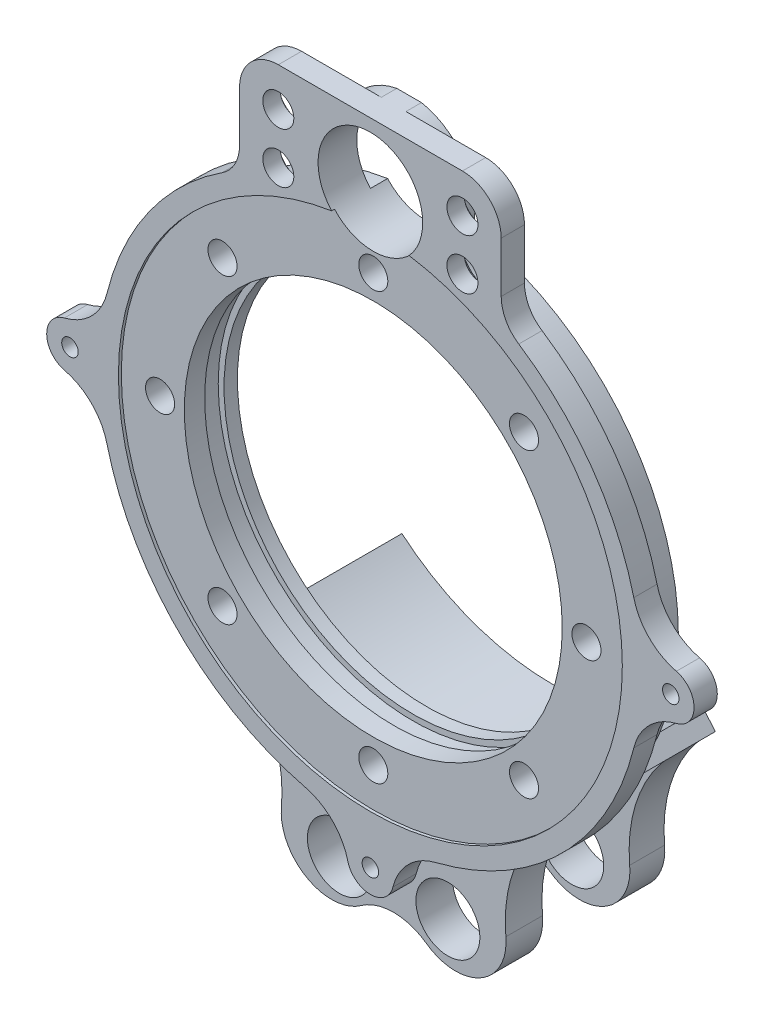
SolidWorks part; units mm, degrees
ref_plane "Front Plane" through (0, 0, 0) normal (0, 0, 1) x (1, 0, 0)
ref_plane "Top Plane" through (0, 0, 0) normal (0, 1, 0) x (1, 0, 0)
ref_plane "Right Plane" through (0, 0, 0) normal (1, 0, 0) x (0, 0, -1)
sketch "Sketch2" plane through (0, 0, 0) normal (0, 0, 1) x (1, 0, 0)
  circle A0 centre (0, 0) radius 140
  circle A1 centre (0, 0) radius 130
  dimension "D1" = 280
  dimension "D2" = 260
extrude "ВнешняяОкружность" add sketch "Sketch2" against normal blind 12
sketch "Sketch3" plane through (0, 0, 0) normal (0, 0, 1) x (1, 0, 0)
  circle A0 centre (0, 0) radius 130
  circle A1 centre (0, 0) radius 97.5
  circle A2 centre (0, 0) radius 130 construction
  dimension "D1" = 195
extrude "ВнутренняяОкружность" add sketch "Sketch3" against normal blind 27.4 from offset 1.5 offset against normal yes
sketch "Sketch4" plane through (0, 0, 0) normal (0, 0, 1) x (1, 0, 0)
  line L0 (0, 422.0044) -> (0, -162.0044) construction
  line L1 (-172.5138, 0) -> (190.2581, 0) construction
  line L2 (-67.5, 111.1024) -> (-67.5, 180)
  line L3 (67.5, 111.1024) -> (67.5, 180)
  line L4 (-67.5, 180) -> (67.5, 180)
  circle A0 centre (0, 0) radius 140 construction
  arc A4 (-67.5, 111.1024) -> (67.5, 111.1024) centre (0, 0) cw
  circle A5 centre (0, 0) radius 130 construction
  spline S0 degree 1 poles (-67.5, 180) (-67.5, 122.653) knots 0 0 1 1
  spline S1 degree 1 poles (67.5, 180) (67.5, 122.653) knots 0 0 1 1
  point P10 (0, 130)
  point P13 (0, 180)
  dimension "D1" = 40
  dimension "D2" = 135
extrude "ВерхнееПриспособление" add sketch "Sketch4" against normal up to surface (12 mm away) contours L4 L3 A4 L2 up to face at (130, 0, -12)
fillet "ВерхПриспосОкругл1" radius 20 2 edges at (-67.5, 180, -6) (67.5, 180, -6)
fillet "ВерхПриспосОкругл2" radius 20 2 edges at (67.5, 122.653, -6) (-67.5, 122.653, -6)
sketch "Sketch5" plane through (0, 0, 0) normal (0, 0, 1) x (1, 0, 0)
  line L0 (0, 277.4091) -> (0, -201.1036) construction
  line L1 (47.5, 206.683) -> (47.5, 65.5198) construction
  line L2 (-92.0038, 133.9543) -> (83.972, 133.9543) construction
  line L4 (-47.5, 180) -> (47.5, 180) construction
  line L5 (-92.0038, 160) -> (83.972, 160) construction
  line L6 (-47.5, 206.683) -> (-47.5, 65.5198) construction
  circle A0 centre (0, 146.6) radius 27
  circle A1 centre (-47.5, 160) radius 8
  circle A2 centre (47.5, 160) radius 8
  circle A3 centre (-47.5, 133.9543) radius 8
  circle A4 centre (47.5, 133.9543) radius 8
  dimension "D1" = 54
  dimension "D3" = 16
  dimension "D4" = 16
  dimension "D5" = 16
  dimension "D6" = 16
  dimension "D2" = 6.4
extrude "ВерхПриспосОтверстия" cut sketch "Sketch5" against normal through all both and the other way through all
sketch "Sketch7" plane through (0, 0, 0) normal (0, 0, 1) x (1, 0, 0)
  line L0 (-47.5, 180) -> (47.5, 180) construction
  line L1 (-6.3592, 180) -> (6.3592, 180)
  arc A0 (-6.3592, 180) -> (6.3592, 180) centre (0, 146.6) ccw
  circle A1 centre (0, 146.6) radius 27
  dimension "D1" = 54
  dimension "D2" = 68
extrude "ВерхПриспосСтенка" add sketch "Sketch7" against normal offset from surface (18.5 mm away) 8 from vertex
fillet "ВерхПриспосСтенкаОкругл" radius 20 2 edges at (-27.78, 126.9971, -16) (27.78, 126.9971, -16)
sketch "Sketch8" plane through (0, 0, -12) normal (0, 0, -1) x (-1, 0, 0)
  circle A0 centre (-47.5, 160) radius 12
  circle A1 centre (-47.5, 160) radius 8
  circle A2 centre (-47.5, 133.9543) radius 8
  circle A3 centre (-47.5, 133.9543) radius 12
  circle A4 centre (47.5, 160) radius 8
  circle A5 centre (47.5, 160) radius 12
  circle A6 centre (47.5, 133.9543) radius 8
  circle A7 centre (47.5, 133.9543) radius 12
  circle A8 centre (47.5, 160) radius 8 construction
  circle A9 centre (47.5, 133.9543) radius 8 construction
  circle A10 centre (-47.5, 160) radius 8 construction
  circle A11 centre (-47.5, 133.9543) radius 8 construction
  dimension "D1" = 24
  dimension "D2" = 24
  dimension "D3" = 24
  dimension "D4" = 24
extrude "ВерхПриспосОтверстияПазы" cut sketch "Sketch8" against normal offset from surface (3 mm away) 3 up to face at (55.5, 133.9543, -12)
sketch "Sketch9" plane through (0, 0, 0) normal (0, 0, 1) x (1, 0, 0)
  line L0 (0, 219.1869) -> (0, -189.3726) construction
  circle A2 centre (0, 110) radius 7.5
  circle A10 centre (77.7817, 77.7817) radius 7.5
  circle A11 centre (110, 0) radius 7.5
  circle A12 centre (77.7817, -77.7817) radius 7.5
  circle A13 centre (0, -110) radius 7.5
  circle A14 centre (-77.7817, -77.7817) radius 7.5
  circle A15 centre (-110, 0) radius 7.5
  circle A16 centre (-77.7817, 77.7817) radius 7.5
  point P21 (0, 0)
  point P22 (-3.6213, 1.5)
  dimension "D1" = 15
  dimension "D3" = 8
  dimension "D2" = 110
extrude "ВнутренОкружОтверстия" cut sketch "Sketch9" against normal through all both and the other way through all
sketch "Sketch10" plane through (0, 0, 0) normal (0, 0, 1) x (1, 0, 0)
  line L0 (162.2706, 0) -> (-214.4388, 0) construction
  line L1 (-155, 12) -> (-139.4848, 12)
  line L2 (-155, -12) -> (-139.4848, -12)
  line L3 (-139.4848, 12) -> (-139.4848, -12)
  line L4 (-12, -139.4848) -> (12, -139.4848)
  line L5 (-12, -155) -> (-12, -139.4848)
  line L6 (12, -155) -> (12, -139.4848)
  line L7 (139.4848, -12) -> (139.4848, 12)
  line L8 (155, -12) -> (139.4848, -12)
  line L9 (155, 12) -> (139.4848, 12)
  line L10 (12, 139.4848) -> (-12, 139.4848) [skipped]
  line L11 (12, 155) -> (12, 139.4848) [skipped]
  line L12 (-12, 155) -> (-12, 139.4848) [skipped]
  circle A0 centre (-155, 0) radius 4.25
  arc A1 (-155, 12) -> (-155, -12) centre (-155, 0) ccw
  arc A2 (-76.5625, 117.21) -> (76.5625, 117.21) centre (0, 0) ccw construction
  arc A3 (-12, -155) -> (12, -155) centre (0, -155) ccw
  circle A4 centre (0, -155) radius 4.25
  arc A5 (155, -12) -> (155, 12) centre (155, 0) ccw
  circle A6 centre (155, 0) radius 4.25
  arc A7 (12, 155) -> (-12, 155) centre (0, 155) ccw [skipped]
  circle A8 centre (0, 155) radius 4.25 [skipped]
  point P33 (0, 0)
  dimension "D1" = 8.5
  dimension "D2" = 24
  dimension "D3" = 155
  dimension "D4" = 4
extrude "ВнешнОкружКрепления" add sketch "Sketch10" against normal up to surface (12 mm away) up to face at (-59.5, 160, -12)
fillet "ВнешнОкружКрепленияОкругл" radius 30 6 edges at (-139.4848, -12, -6) (-139.4848, 12, -6) (139.4848, 12, -6) (139.4848, -12, -6) (12, -139.4848, -6) (-12, -139.4848, -6)
sketch "Sketch12" plane through (0, 0, -1.5) normal (0, 0, 1) x (1, 0, 0)
  circle A0 centre (0, 0) radius 100.5
  dimension "D1" = 201
extrude "ВнутренОкружВырезВнутри" cut sketch "Sketch12" against normal blind 10 from offset 10.5 offset against normal yes
sketch "Sketch13" plane through (0, 0, -28.9) normal (0, 0, -1) x (-1, 0, 0)
  line L0 (0, 233.5237) -> (0, -120) construction
  line L1 (-58, 233.5237) -> (-58, -105.0524) construction
  line L2 (58, 233.5237) -> (58, -105.0524) construction
  line L3 (-120.3131, -170) -> (-11.5, -170) construction
  line L4 (0, 0) -> (-132.6044, -156.3364) construction
  line L5 (-84.0906, -99.1402) -> (-77.6221, -91.514)
  line L6 (-148.4863, -94) -> (143.1402, -94) construction
  line L7 (0, 0) -> (132.6044, -156.3364) construction
  line L8 (84.0906, -99.1402) -> (77.6221, -91.514)
  line L9 (-58, -148.643) -> (-58, -221.1325) construction
  line L10 (0, -181) -> (0, -221.1325) construction
  line L11 (58, -148.643) -> (58, -221.1325) construction
  line L12 (57.5657, -170) -> (119.8752, -170) construction
  circle A0 centre (0, -210) radius 29 construction
  circle A1 centre (-28, -170) radius 16.5
  circle A2 centre (28, -170) radius 16.5
  arc A3 (-57.8982, -162.9684) -> (-16.8727, -186.4138) centre (-32, -165.2675) ccw
  arc A4 (16.8727, -186.4138) -> (57.8982, -162.9684) centre (32, -165.2675) ccw
  circle A6 centre (-132.6044, -156.3364) radius 75 construction
  circle A8 centre (132.6044, -156.3364) radius 75 construction
  arc A9 (-19.9926, 128.4535) -> (19.9926, 128.4535) centre (0, 0) ccw construction
  circle A10 centre (0, 0) radius 120 construction
  arc A11 (84.0906, -99.1402) -> (57.8982, -162.9684) centre (132.6044, -156.3364) ccw
  arc A13 (-46.4591, 121.4148) -> (46.4591, 121.4148) centre (0, 0) ccw construction
  arc A14 (-77.6221, -91.514) -> (77.6221, -91.514) centre (0, 0) ccw
  arc A15 (-84.0906, -99.1402) -> (-57.8982, -162.9684) centre (-132.6044, -156.3364) cw
  arc A16 (-16.8727, -186.4138) -> (16.8727, -186.4138) centre (0, -210) cw
  dimension "D1" = 58
  dimension "D3" = 170
  dimension "D6" = 33
  dimension "D7" = 28
  dimension "D9" = 52
  dimension "D10" = 32
  dimension "D12" = 32
  dimension "D13" = 150
  dimension "D5" = 58
  dimension "D11" = 150
  dimension "D14" = 240
  dimension "D2" = 58
  dimension "D4" = 210
  dimension "D8" = 28
  dimension "D15" = 94
extrude "НижнееПриспособление" add sketch "Sketch13" along normal blind 65 and the other way up to surface other way up to face at (-59.5, 160, -12)
sketch "Sketch17" plane through (0, 0, -93.9) normal (0, 0, -1) x (-1, 0, 0)
  circle A0 centre (0, 0) radius 130
extrude "НижнПриспосВырез" cut sketch "Sketch17" against normal blind 45 from offset 18 flip side to cut
